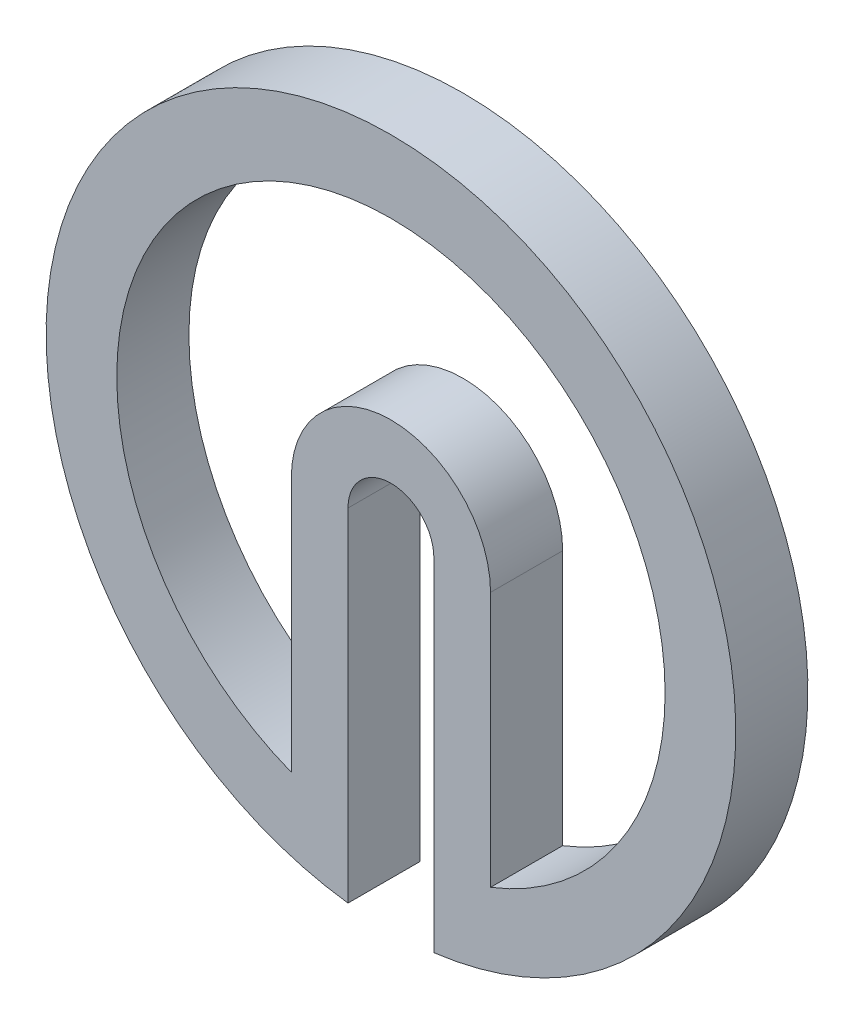
SolidWorks part; units mm, degrees
ref_plane "Front Plane" through (0, 0, 0) normal (0, 0, 1) x (1, 0, 0)
ref_plane "Top Plane" through (0, 0, 0) normal (0, 1, 0) x (1, 0, 0)
ref_plane "Right Plane" through (0, 0, 0) normal (1, 0, 0) x (0, 0, -1)
sketch "Sketch1" plane through (0, 0, 0) normal (0, 0, 1) x (1, 0, 0)
  line L0 (-3.175, 0) -> (-3.175, -25.3016)
  line L1 (3.175, 0) -> (3.175, -25.3016)
  arc A0 (3.175, -25.3016) -> (-3.175, -25.3016) centre (0, 0) ccw
  arc A1 (3.175, 0) -> (-3.175, 0) centre (0, 0) ccw
  dimension "D1" = 51
  dimension "D2" = 6.35
extrude "Boss-Extrude1" add sketch "Sketch1" against normal blind 5.334
sketch "Sketch3" plane through (0, 0, 0) normal (0, 0, 1) x (1, 0, 0)
  line L0 (0, -27.9489) -> (0, 27.687) construction
  line L1 (-7.3658, -0.131) -> (-7.3658, -19.0198)
  line L2 (7.3658, -0.131) -> (7.3658, -19.0198)
  arc A0 (7.3658, -19.0198) -> (-7.3658, -19.0198) centre (0, -0.131) ccw
  arc A1 (7.3658, -0.131) -> (-7.3658, -0.131) centre (0, -0.131) ccw
extrude "Cut-Extrude1" cut sketch "Sketch3" against normal through all
